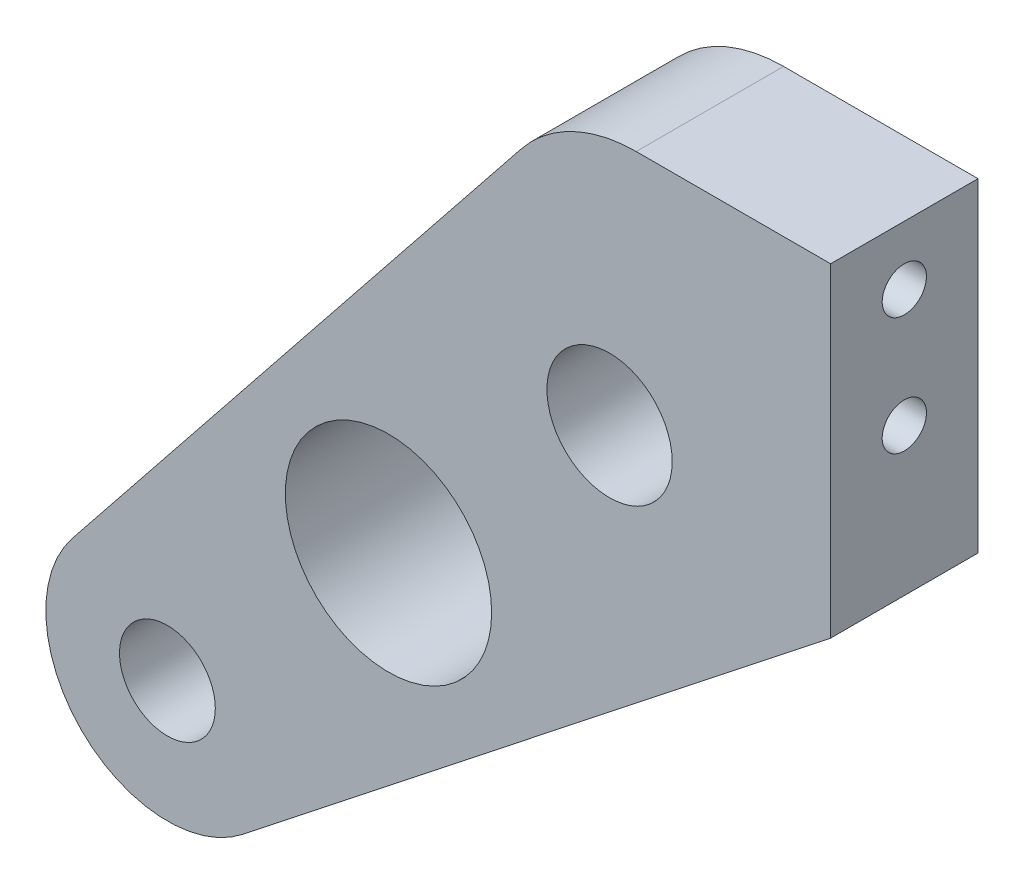
SolidWorks part; units mm, degrees
material "ABS PC"
ref_plane "Спереди" through (0, 0, 0) normal (0, 0, 1) x (1, 0, 0)
ref_plane "Сверху" through (0, 0, 0) normal (0, 1, 0) x (1, 0, 0)
ref_plane "Справа" through (0, 0, 0) normal (1, 0, 0) x (0, 0, -1)
sketch "Sketch1" plane through (0, 0, 0) normal (0, 0, 1) x (1, 0, 0)
  line L0 (5.1105, -6.4765) -> (45, 25)
  line L1 (45, 25) -> (45, 47)
  line L2 (45, 47) -> (27, 47)
  line L3 (27, 47) -> (-6.4448, 5.1505)
  line L4 (0, 0) -> (30, 30) construction
  circle A0 centre (0, 0) radius 3.25
  circle A1 centre (30, 30) radius 4.25
  arc A3 (-6.4448, 5.1505) -> (5.1105, -6.4765) centre (0, 0) ccw
  circle A4 centre (15, 15) radius 7
  dimension "D1" = 30
  dimension "D2" = 30
  dimension "D3" = 6.5
  dimension "D4" = 8.5
  dimension "D5" = 5
  dimension "D6" = 22
  dimension "D9" = 14
  dimension "D7" = 15
  dimension "D8" = 5
  dimension "D10" = 18
extrude "Boss-Extrude1" add sketch "Sketch1" along normal blind 10
sketch "Sketch2" plane through (45, 0, 0) normal (1, 0, 0) x (0, 0, -1)
  line L0 (-10, 25) -> (-10, 47) construction
  line L1 (-10, 47) -> (0, 47) construction
  circle A0 centre (-5, 43) radius 1.5
  circle A1 centre (-5, 35) radius 1.5
  dimension "D1" = 3
  dimension "D2" = 5
  dimension "D3" = 4
  dimension "D4" = 8
extrude "Cut-Extrude1" cut sketch "Sketch2" against normal blind 10
fillet "Fillet1" radius 10 1 edges at (27, 47, 5)
